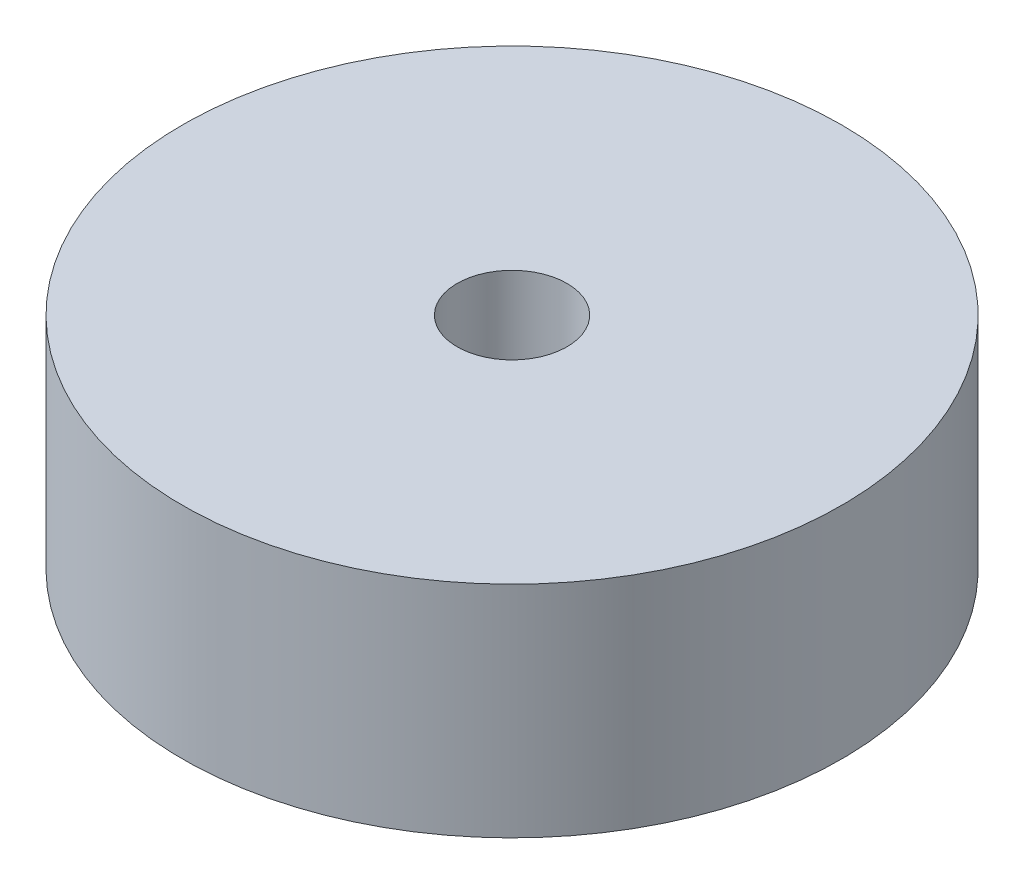
SolidWorks part; units mm, degrees
ref_plane "Front Plane" through (0, 0, 0) normal (0, 0, 1) x (1, 0, 0)
ref_plane "Top Plane" through (0, 0, 0) normal (0, 1, 0) x (1, 0, 0)
ref_plane "Right Plane" through (0, 0, 0) normal (1, 0, 0) x (0, 0, -1)
sketch "Sketch2" plane through (0, 0, 0) normal (0, 1, 0) x (1, 0, 0)
  circle A0 centre (0, 0) radius 150
  circle A1 centre (0, 0) radius 25
  dimension "D1" = 300
extrude "Boss-Extrude1" add sketch "Sketch2" along normal blind 100 contours A1 | A0
